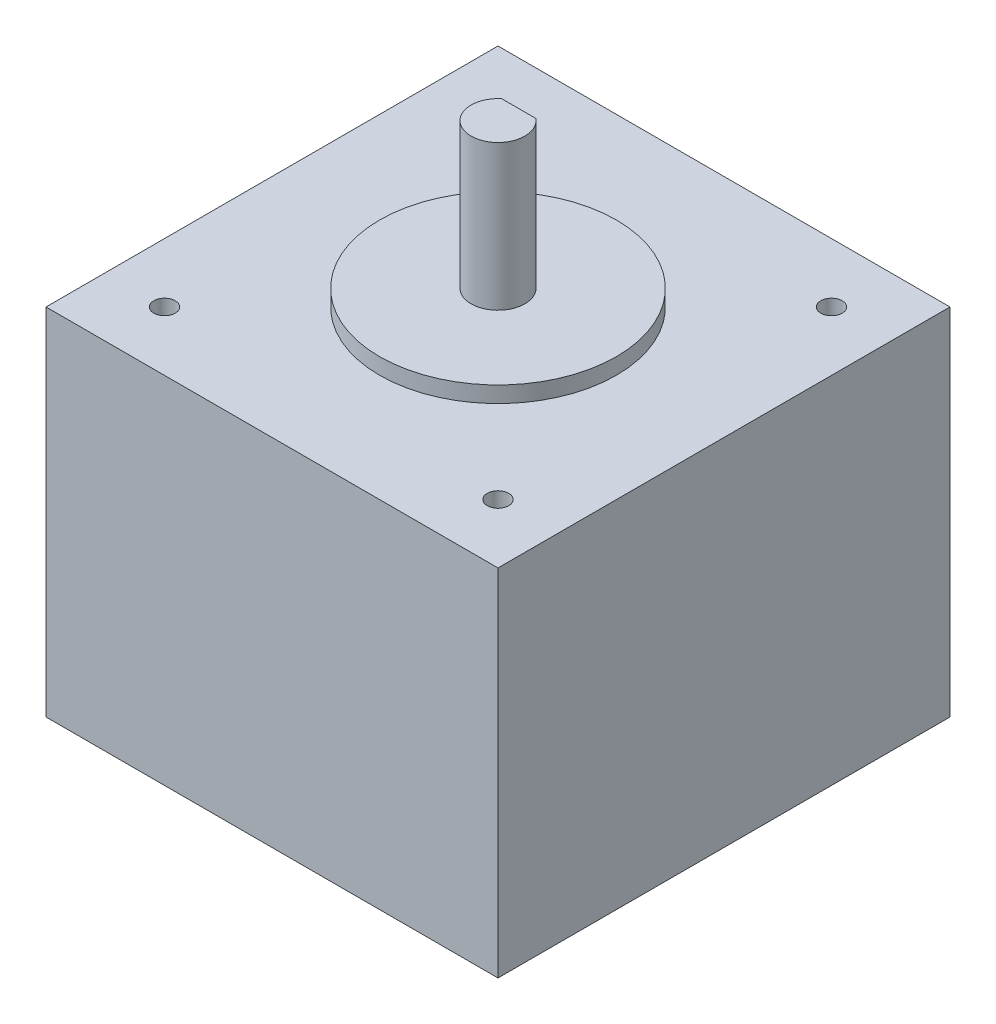
SolidWorks part; units mm, degrees
ref_plane "Front Plane" through (0, 0, 0) normal (0, 0, 1) x (1, 0, 0)
ref_plane "Top Plane" through (0, 0, 0) normal (0, 1, 0) x (1, 0, 0)
ref_plane "Right Plane" through (0, 0, 0) normal (1, 0, 0) x (0, 0, -1)
sketch "Sketch1" plane through (0, 0, 0) normal (0, 1, 0) x (1, 0, 0)
  line L1 (0, 0) -> (42, 0)
  line L2 (0, 0) -> (0, 42)
  line L3 (0, 42) -> (42, 42)
  line L4 (42, 0) -> (42, 42)
  dimension "D1" = 42
extrude "Boss-Extrude1" add sketch "Sketch1" along normal blind 33
sketch "Sketch2" plane through (0, 33, 0) normal (0, 1, 0) x (1, 0, 0)
  line L0 (21, 42) -> (21, 0) construction
  line L1 (42, 42) -> (0, 42) construction
  line L2 (0, 0) -> (42, 0) construction
  line L3 (0, 21) -> (42, 21) construction
  line L4 (0, 42) -> (0, 0) construction
  line L5 (42, 0) -> (42, 42) construction
  line L6 (5.505, 5.505) -> (21, 5.505) construction
  line L7 (5.505, 36.495) -> (21, 36.495) construction
  line L8 (36.495, 5.505) -> (36.495, 21) construction
  line L9 (36.495, 36.495) -> (36.495, 21) construction
  line L10 (36.495, 36.495) -> (21, 36.495) construction
  line L11 (5.505, 5.505) -> (5.505, 21) construction
  line L12 (5.505, 36.495) -> (5.505, 21) construction
  line L13 (36.495, 5.505) -> (21, 5.505) construction
  circle A0 centre (5.505, 36.495) radius 1
  circle A1 centre (36.495, 36.495) radius 1
  circle A2 centre (36.495, 5.505) radius 1
  circle A3 centre (5.505, 5.505) radius 1
  dimension "D2" = 2
  dimension "D1" = 30.99
extrude "Cut-Extrude1" cut sketch "Sketch2" against normal blind 3.5
sketch "Sketch3" plane through (0, 33, 0) normal (0, 1, 0) x (1, 0, 0)
  line L0 (0, 21) -> (42, 21) construction
  line L1 (0, 42) -> (0, 0) construction
  line L2 (42, 0) -> (42, 42) construction
  circle A0 centre (21, 21) radius 11
  dimension "D1" = 22
extrude "Boss-Extrude2" add sketch "Sketch3" along normal blind 1.5
sketch "Sketch4" plane through (0, 34.5, 0) normal (0, 1, 0) x (1, 0, 0)
  line L0 (10, 21) -> (32, 21) construction
  circle A0 centre (21, 21) radius 11 construction
  circle A1 centre (21, 21) radius 2.5
  dimension "D1" = 5
extrude "Boss-Extrude3" add sketch "Sketch4" along normal blind 13.5
sketch "Sketch5" plane through (0, 48, 0) normal (0, 1, 0) x (1, 0, 0)
  line L0 (19.4109, 22.93) -> (22.5891, 22.93)
  line L1 (21, 18.5) -> (23.7751, 18.5) construction
  circle A0 centre (21, 21) radius 2.5 construction
  arc A1 (19.4109, 22.93) -> (22.5891, 22.93) centre (21, 21) cw
  circle M3 centre (21, 21) radius 2.5
  dimension "D1" = 4.43
extrude "Cut-Extrude2" cut sketch "Sketch5" against normal up to surface (13.5 mm away) contours L0 M3
